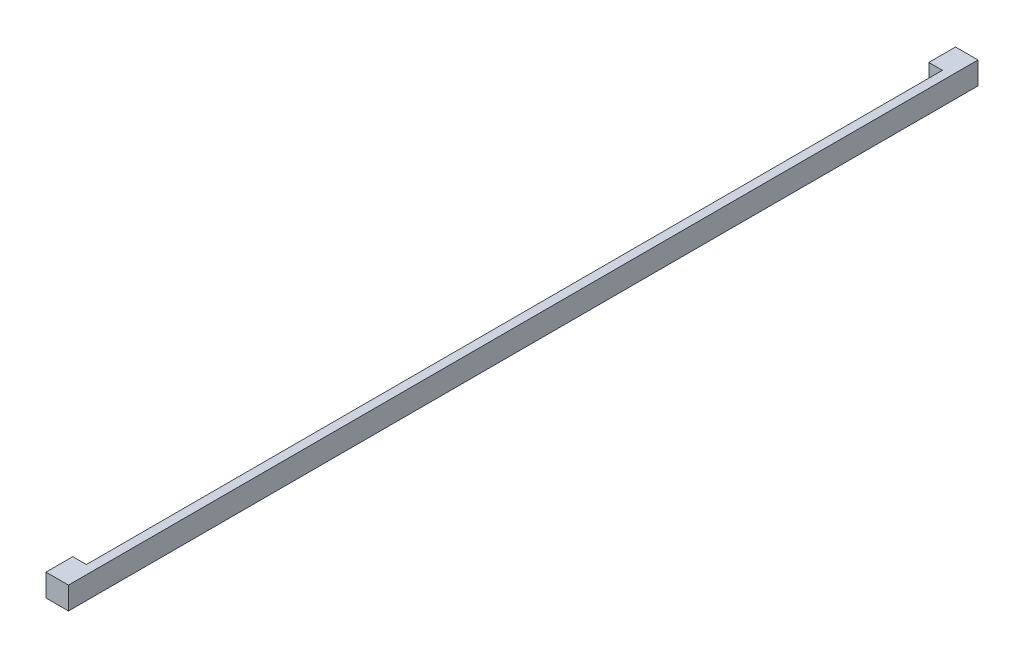
SolidWorks part; units mm, degrees
material "6061 Сплав"
ref_plane "Спереди" through (0, 0, 0) normal (0, 0, 1) x (1, 0, 0)
ref_plane "Сверху" through (0, 0, 0) normal (0, 1, 0) x (1, 0, 0)
ref_plane "Справа" through (0, 0, 0) normal (1, 0, 0) x (0, 0, -1)
sketch "Эскиз1" plane through (0, 0, 0) normal (0, 0, 1) x (1, 0, 0)
  line L1 (-4.2, -4.2) -> (4.2, -4.2)
  line L2 (-4.2, -4.2) -> (-4.2, 4.2)
  line L3 (-4.2, 4.2) -> (4.2, 4.2)
  line L4 (4.2, -4.2) -> (4.2, 4.2)
  line L5 (-4.2, -4.2) -> (4.2, 4.2) construction
  line L6 (-4.2, 4.2) -> (4.2, -4.2) construction
  point P0 (0, 0)
  dimension "D1" = 8.4
  dimension "D2" = 8.4
extrude "Бобышка-Вытянуть1" add sketch "Эскиз1" along normal blind 340
sketch "Эскиз3" plane through (0, 4.2, 0) normal (0, 1, 0) x (1, 0, 0)
  line L0 (4.2, -340) -> (-4.2, -340) construction
  line L1 (-14.8601, -10) -> (0.9, -10)
  line L2 (-14.8601, -10) -> (-14.8601, -330)
  line L3 (-14.8601, -330) -> (0.9, -330)
  line L4 (0.9, -10) -> (0.9, -330)
  line L5 (4.2, 0) -> (-4.2, 0) construction
  line L6 (4.2, -340) -> (4.2, 0) construction
  dimension "D1" = 10
  dimension "D2" = 10
  dimension "D3" = 3.3
extrude "Вырез-Вытянуть1" cut sketch "Эскиз3" against normal blind 5.1
